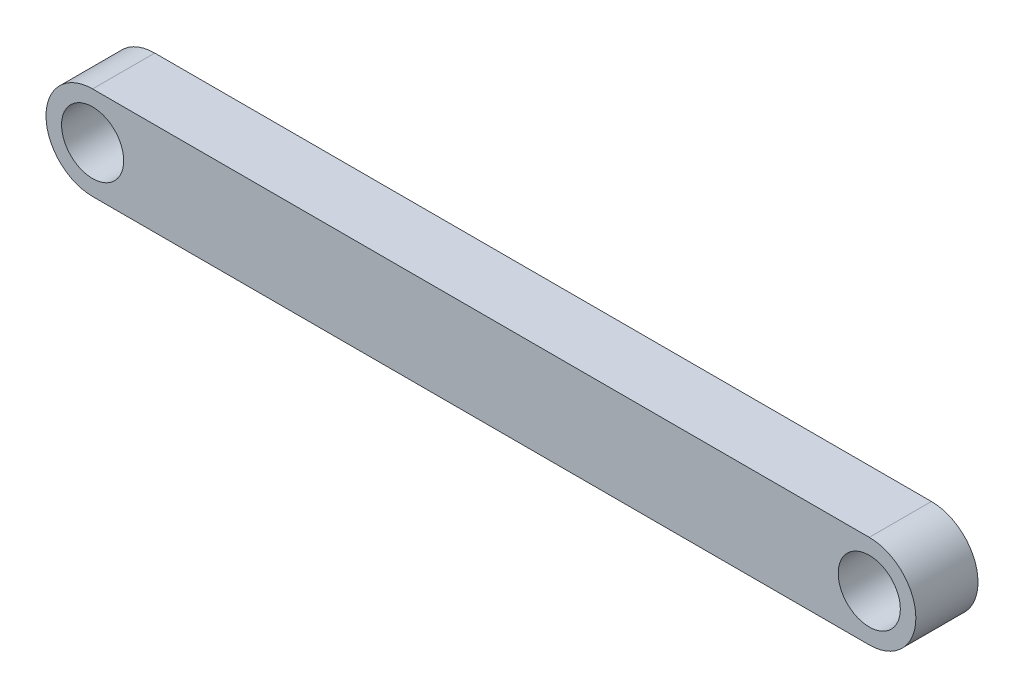
SolidWorks part; units mm, degrees
ref_plane "Спереди" through (0, 0, 0) normal (0, 0, 1) x (1, 0, 0)
ref_plane "Сверху" through (0, 0, 0) normal (0, 1, 0) x (1, 0, 0)
ref_plane "Справа" through (0, 0, 0) normal (1, 0, 0) x (0, 0, -1)
sketch "Эскиз1" plane through (0, 0, 0) normal (0, 0, 1) x (1, 0, 0)
  line L0 (-75, 0) -> (-325, 0) construction
  line L1 (-75, -15) -> (-325, -15)
  line L2 (-75, 15) -> (-325, 15)
  circle A0 centre (-75, 0) radius 10 construction
  circle A1 centre (-75, 0) radius 10
  arc A2 (-75, -15) -> (-75, 15) centre (-75, 0) ccw
  arc A3 (-325, 15) -> (-325, -15) centre (-325, 0) ccw
  circle A4 centre (-325, 0) radius 10
  arc A5 (-73.9488, 14.9631) -> (-76.0512, -14.9631) centre (-75, 0) ccw construction
  point P4 (-200, 0)
  dimension "D1" = 250
extrude "Бобышка-Вытянуть1" add sketch "Эскиз1" along normal blind 20
